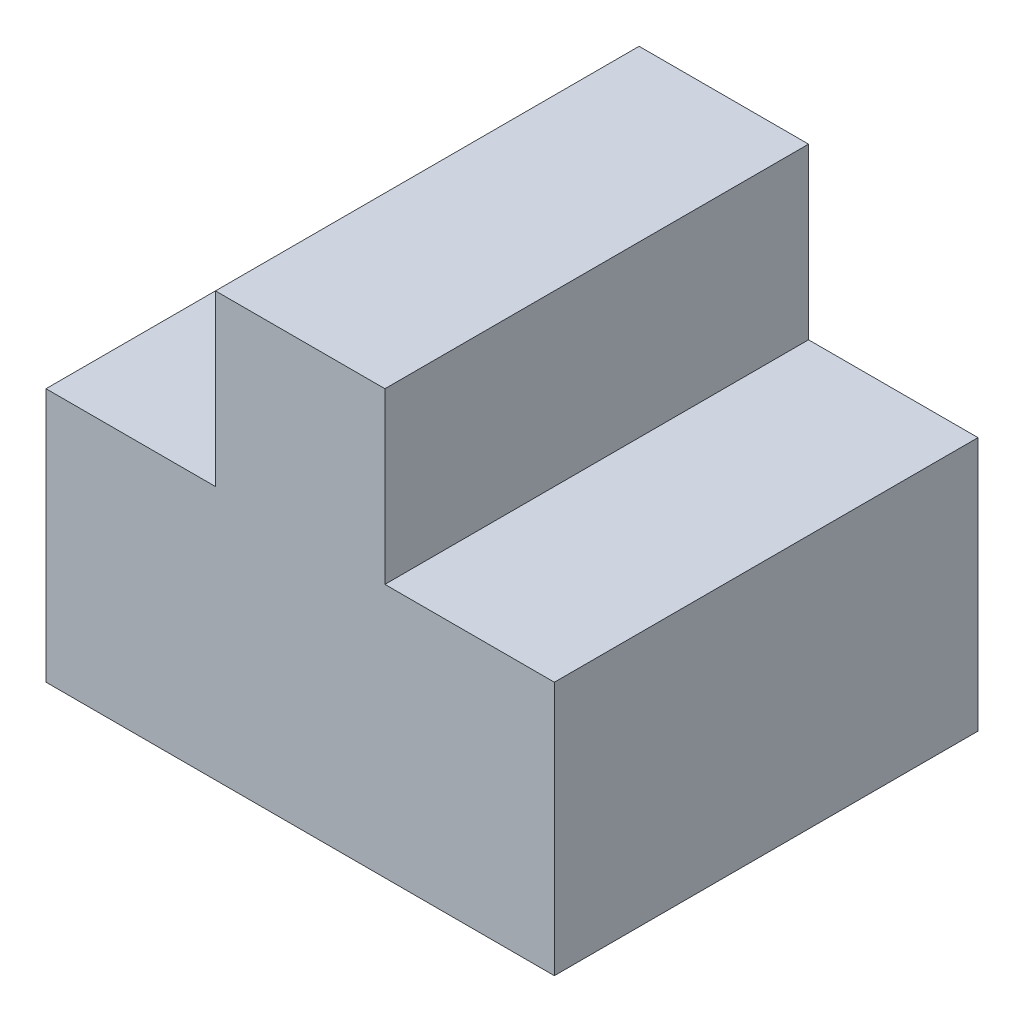
SolidWorks part; units mm, degrees
ref_plane "Front Plane" through (0, 0, 0) normal (0, 0, 1) x (1, 0, 0)
ref_plane "Top Plane" through (0, 0, 0) normal (0, 1, 0) x (1, 0, 0)
ref_plane "Right Plane" through (0, 0, 0) normal (1, 0, 0) x (0, 0, -1)
sketch "Esquisse1" plane through (0, 0, 0) normal (0, 0, 1) x (1, 0, 0)
  line L0 (0, 0) -> (60, 0)
  line L1 (60, 0) -> (60, 30)
  line L2 (60, 30) -> (40, 30)
  line L3 (40, 30) -> (40, 50)
  line L4 (40, 50) -> (20, 50)
  line L5 (20, 50) -> (20, 30)
  line L6 (20, 30) -> (0, 30)
  line L7 (0, 30) -> (0, 0)
  dimension "D1" = 20
  dimension "D2" = 20
  dimension "D3" = 30
extrude "Extrusion1" add sketch "Esquisse1" along normal blind 50
